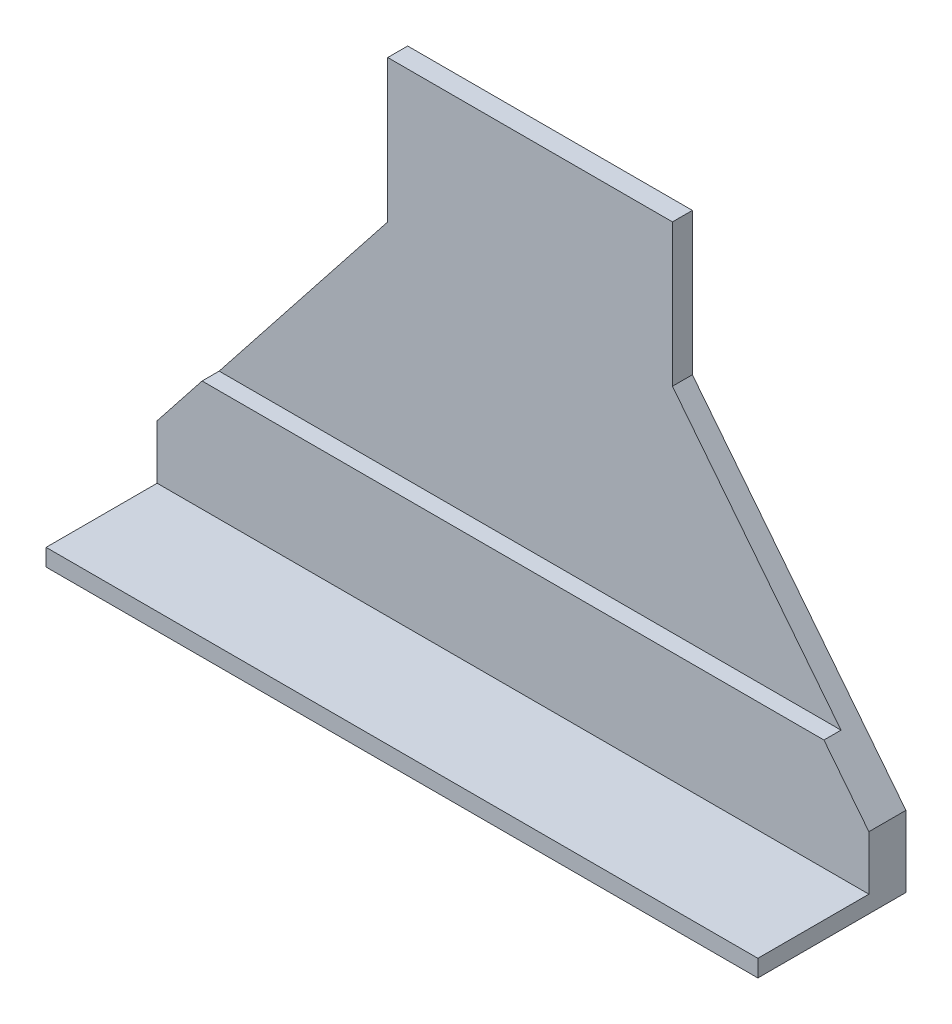
SolidWorks part; units mm, degrees
ref_plane "前视基准面" through (0, 0, 0) normal (0, 0, 1) x (1, 0, 0)
ref_plane "上视基准面" through (0, 0, 0) normal (0, 1, 0) x (1, 0, 0)
ref_plane "右视基准面" through (0, 0, 0) normal (1, 0, 0) x (0, 0, -1)
sketch "草图1" plane through (0, 0, 0) normal (0, 0, 1) x (1, 0, 0)
  line L1 (0, 0) -> (250, 0)
  line L2 (0, 0) -> (-250, 0)
  line L3 (-250, 0) -> (-250, 50)
  line L4 (250, 0) -> (250, 50)
  line L5 (0, 340) -> (100, 340)
  line L6 (0, 340) -> (-100, 340)
  line L7 (-100, 340) -> (-100, 240)
  line L8 (100, 340) -> (100, 240)
  line L9 (-100, 240) -> (-250, 50)
  line L10 (100, 240) -> (250, 50)
  dimension "D1" = 250
extrude "凸台-拉伸1" add sketch "草图1" along normal blind 14
sketch "草图2" plane through (0, 0, 14) normal (0, 0, 1) x (1, 0, 0)
  line L0 (-100, 290) -> (100, 290) construction
  line L1 (-100, 340) -> (-100, 240) construction
  line L2 (100, 240) -> (100, 340) construction
  line L3 (100, 340) -> (-100, 340) construction
  line L4 (0, 340) -> (0, 0) construction
  line L5 (-250, 50) -> (-250, 0) construction
  line L6 (-56, 340) -> (-56, 0) construction
  line L7 (-250, 0) -> (250, 0) construction
  dimension "D1" = 50
  dimension "D2" = 250
  dimension "D3" = 56
sketch "草图3" plane through (0, 0, 14) normal (0, 0, 1) x (1, 0, 0)
  line L0 (-100, 290) -> (100, 290) construction
  line L1 (-56, 340) -> (-56, 0) construction
  circle A0 centre (-56, 290) radius 13
extrude "切除-拉伸1" cut sketch "草图3" against normal through all
pattern_linear "阵列(线性)1" count 3 spacing 80 along (0, -1, 0) of "切除-拉伸1"
mirror "镜向1" about plane through (0, 0, 0) normal (1, 0, 0) of "阵列(线性)1", "切除-拉伸1"
sketch "草图6" plane through (0, 0, 14) normal (0, 0, 1) x (1, 0, 0)
  line L0 (-218.4211, 90) -> (218.4211, 90) construction
  line L1 (-100, 240) -> (-250, 50) construction
  line L2 (250, 50) -> (100, 240) construction
  line L3 (-250, 0) -> (250, 0) construction
  dimension "D1" = 90
extrude "凸台-拉伸2" add sketch "草图6" along normal blind 12
sketch "草图7" plane through (0, 0, 26) normal (0, 0, 1) x (1, 0, 0)
  line L0 (-250, 50) -> (250, 50) construction
  line L1 (-250, 50) -> (-250, 0) construction
  line L2 (250, 0) -> (250, 50) construction
  line L3 (-250, 0) -> (250, 0) construction
  line L4 (-130, 340) -> (-130, 0) construction
  line L5 (100, 340) -> (-100, 340) construction
  line L6 (-56, 340) -> (-56, 0) construction
  line L7 (-196, 340) -> (-196, 0) construction
  circle A0 centre (-56, 50) radius 13
  circle A1 centre (-130, 50) radius 13
  circle A2 centre (-196, 50) radius 13
  dimension "D1" = 50
  dimension "D2" = 74
  dimension "D3" = 140
extrude "切除-拉伸2" cut sketch "草图7" against normal through all
mirror "镜向2" about plane through (0, 0, 0) normal (1, 0, 0) of "切除-拉伸2"
sketch "草图8" plane through (0, 0, 26) normal (0, 0, 1) x (1, 0, 0)
  line L1 (-250, 0) -> (250, 0)
  line L2 (-250, 0) -> (-250, 12)
  line L3 (-250, 12) -> (250, 12)
  line L4 (250, 0) -> (250, 12)
extrude "凸台-拉伸5" add sketch "草图8" along normal blind 78
sketch "草图9" plane through (0, 0, 0) normal (0, -1, 0) x (1, 0, 0)
  line L0 (-250, 14) -> (250, 14) construction
  line L1 (-250, 104) -> (-250, 0) construction
  line L2 (250, 104) -> (250, 0) construction
  line L3 (-250, 0) -> (250, 0) construction
  line L4 (-250, 55) -> (250, 55) construction
  line L5 (-250, 104) -> (250, 104) construction
  line L6 (-180, 104) -> (-180, 0) construction
  line L7 (-100, 104) -> (-100, 0) construction
  circle A0 centre (-180, 55) radius 13
  circle A1 centre (-100, 55) radius 13
  dimension "D1" = 14
  dimension "D2" = 49
  dimension "D3" = 41
  dimension "D4" = 70
  dimension "D5" = 80
extrude "切除-拉伸3" cut sketch "草图9" against normal through all
mirror "镜向3" about plane through (0, 0, 0) normal (1, 0, 0) of "切除-拉伸3"
sketch "草图10" plane through (0, 0, 14) normal (0, 0, 1) x (1, 0, 0)
  line L0 (-100, 340) -> (100, 340)
  line L1 (100, 340) -> (100, 240)
  line L2 (100, 240) -> (218.4211, 90)
  line L3 (218.4211, 90) -> (-218.4211, 90)
  line L4 (-218.4211, 90) -> (-100, 240)
  line L5 (-100, 240) -> (-100, 340)
extrude "凸台-拉伸6" add sketch "草图10" against normal blind 14
sketch "草图11" plane through (0, 0, 26) normal (0, 0, 1) x (1, 0, 0)
  line L0 (-218.4211, 90) -> (218.4211, 90)
  line L1 (218.4211, 90) -> (250, 50)
  line L2 (250, 50) -> (250, 12)
  line L3 (250, 12) -> (-250, 12)
  line L4 (-250, 12) -> (-250, 50)
  line L5 (-250, 50) -> (-218.4211, 90)
extrude "凸台-拉伸7" add sketch "草图11" against normal blind 26
sketch "草图12" plane through (0, 12, 0) normal (0, 1, 0) x (1, 0, 0)
  line L1 (-250, -26) -> (250, -26)
  line L2 (-250, -26) -> (-250, -104)
  line L3 (-250, -104) -> (250, -104)
  line L4 (250, -26) -> (250, -104)
extrude "凸台-拉伸8" add sketch "草图12" against normal blind 12
